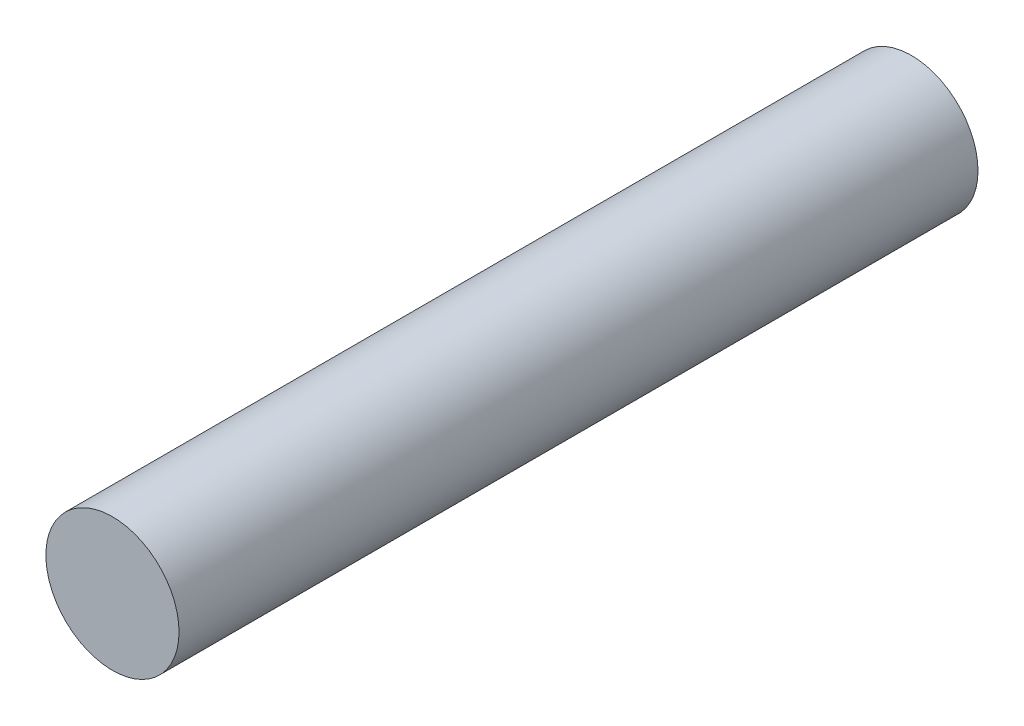
SolidWorks part; units mm, degrees
ref_plane "Front Plane" through (0, 0, 0) normal (0, 0, 1) x (1, 0, 0)
ref_plane "Top Plane" through (0, 0, 0) normal (0, 1, 0) x (1, 0, 0)
ref_plane "Right Plane" through (0, 0, 0) normal (1, 0, 0) x (0, 0, -1)
sketch "Sketch2" plane through (0, 0, 0) normal (0, 0, 1) x (1, 0, 0)
  circle A0 centre (0, 0) radius 0.1875
  dimension "D1" = 0.375
extrude "Boss-Extrude1" add sketch "Sketch2" along normal blind 2.25
